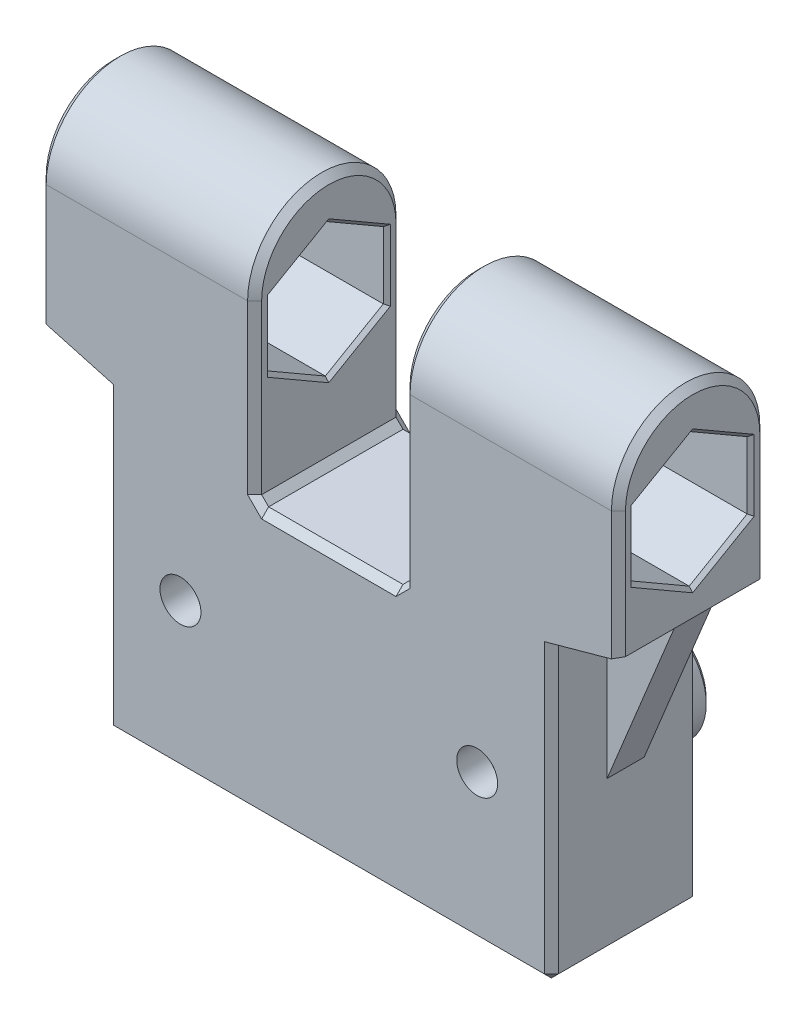
SolidWorks part; units mm, degrees
ref_plane "Front Plane" through (0, 0, 0) normal (0, 0, 1) x (1, 0, 0)
ref_plane "Top Plane" through (0, 0, 0) normal (0, 1, 0) x (1, 0, 0)
ref_plane "Right Plane" through (0, 0, 0) normal (1, 0, 0) x (0, 0, -1)
sketch "Sketch1" plane through (0, 0, 0) normal (0, 1, 0) x (1, 0, 0)
  line L0 (12.7, 0) -> (-12.7, 0) construction
  line L1 (0, 0) -> (0, 3.6469) construction
  line L3 (19.05, -6.35) -> (-19.05, -6.35)
  line L4 (19.05, -6.35) -> (19.05, 6.35)
  line L5 (19.05, 6.35) -> (-19.05, 6.35)
  line L6 (-19.05, -6.35) -> (-19.05, 6.35)
  line L7 (19.05, -6.35) -> (-19.05, 6.35) construction
  line L8 (19.05, 6.35) -> (-19.05, -6.35) construction
  circle A0 centre (12.7, 0) radius 4.05
  circle A1 centre (-12.7, 0) radius 4.05
  point P4 (0, 0)
  dimension "D2" = 8.1
  dimension "D1" = 25.4
  dimension "D3" = 38.1
  dimension "D4" = 12.7
extrude "Boss-Extrude1" add sketch "Sketch1" along normal blind 25.4
sketch "Sketch5" plane through (0, 0, 6.35) normal (0, 0, 1) x (1, 0, 0)
  line L0 (19.05, 12.7) -> (-19.05, 12.7) construction
  line L1 (19.05, 25.4) -> (19.05, 0) construction
  line L2 (-19.05, 25.4) -> (-19.05, 0) construction
  line L3 (0, 0) -> (0, 25.4) construction
  line L4 (-19.05, 0) -> (19.05, 0) construction
  line L5 (-19.05, 25.4) -> (19.05, 25.4) construction
  line L6 (12.7, 0) -> (12.7, 25.4) construction
  circle A0 centre (12.7, 12.7) radius 6.35
  circle A1 centre (-12.7, 12.7) radius 6.35
  circle A2 centre (12.7, 12.7) radius 1.7526
  circle A3 centre (-12.7, 12.7) radius 1.7526
  dimension "D2" = 12.7
  dimension "D3" = 3.5052
  dimension "D1" = 12.7
extrude "Cut-Extrude2" cut sketch "Sketch5" against normal through all contours A2 | A3
sketch "Sketch6" plane through (0, 25.4, 0) normal (0, 1, 0) x (1, 0, 0)
  line L0 (0, 6.35) -> (0, -6.35) construction
  line L1 (19.05, 6.35) -> (-19.05, 6.35) construction
  line L2 (-19.05, -6.35) -> (19.05, -6.35) construction
  line L4 (24.792, -6.35) -> (-24.792, -6.35)
  line L5 (24.792, -6.35) -> (24.792, 6.35)
  line L6 (24.792, 6.35) -> (-24.792, 6.35)
  line L7 (-24.792, -6.35) -> (-24.792, 6.35)
  line L8 (24.792, -6.35) -> (-24.792, 6.35) construction
  line L9 (24.792, 6.35) -> (-24.792, -6.35) construction
  point P6 (0, 0)
  dimension "D1" = 49.584
extrude "Boss-Extrude4" add sketch "Sketch6" along normal blind 19.05
sketch "Sketch7" plane through (-24.792, 0, 0) normal (-1, 0, 0) x (0, 0, 1)
  line L0 (0, 25.4) -> (0, 44.45) construction
  line L1 (-6.35, 25.4) -> (6.35, 25.4) construction
  line L2 (-6.35, 44.45) -> (6.35, 44.45) construction
  line L3 (-6.35, 34.925) -> (6.35, 34.925) construction
  line L4 (-6.35, 44.45) -> (-6.35, 25.4) construction
  line L5 (6.35, 44.45) -> (6.35, 25.4) construction
  line L7 (0, 40.6552) -> (-4.9625, 37.7901)
  line L8 (-4.9625, 37.7901) -> (-4.9625, 32.0599)
  line L9 (-4.9625, 32.0599) -> (0, 29.1948)
  line L10 (0, 29.1948) -> (4.9625, 32.0599)
  line L11 (4.9625, 32.0599) -> (4.9625, 37.7901)
  line L12 (4.9625, 37.7901) -> (0, 40.6552)
  circle A0 centre (0, 34.925) radius 4.9625 construction
  dimension "D1" = 9.925
extrude "Cut-Extrude3" cut sketch "Sketch7" against normal through all
sketch "Sketch8" plane through (-24.792, 0, 0) normal (-1, 0, 0) x (0, 0, 1)
  line L0 (4.9625, 37.7901) -> (-4.9625, 37.7901) construction
  line L1 (-6.35, 37.7901) -> (-6.35, 44.45)
  line L2 (-6.35, 44.45) -> (6.35, 44.45)
  line L3 (6.35, 44.45) -> (6.35, 37.7901)
  arc A0 (6.35, 37.7901) -> (-6.35, 37.7901) centre (0, 37.7901) ccw
extrude "Cut-Extrude4" cut sketch "Sketch8" against normal through all
sketch "Sketch9" plane through (0, 0, -6.35) normal (0, 0, -1) x (-1, 0, 0)
  line L0 (0, 37.7901) -> (0, 0) construction
  line L1 (-24.792, 37.7901) -> (24.792, 37.7901) construction
  line L2 (19.05, 25.4) -> (24.792, 26.9875)
  line L3 (24.792, 37.7901) -> (24.792, 25.4) construction
  line L4 (24.792, 26.9875) -> (24.792, 25.4)
  line L5 (24.792, 25.4) -> (19.05, 25.4)
  line L6 (-24.792, 25.4) -> (-19.05, 25.4)
  line L7 (-24.792, 26.9875) -> (-24.792, 25.4)
  line L8 (-19.05, 25.4) -> (-24.792, 26.9875)
  dimension "D1" = 1.5875
extrude "Cut-Extrude5" cut sketch "Sketch9" against normal through all
chamfer "Chamfer1" distance 0.6 angle 45 17 edges at (19.05, 0, 0) (24.792, 32.3888, 6.35) (24.792, 44.1401, 0) (24.792, 32.3888, -6.35) (-24.792, 32.3888, 6.35) (-24.792, 44.1401, 0) (-24.792, 32.3888, -6.35) (0, 0, 6.35) (0, 0, -6.35) (-19.05, 0, 0)
sketch "Sketch10" plane through (0, 0, 6.35) normal (0, 0, 1) x (1, 0, 0)
  line L0 (0, 0.6) -> (0, 37.7901) construction
  line L1 (-18.45, 0.6) -> (18.45, 0.6) construction
  line L2 (24.192, 37.7901) -> (-24.192, 37.7901) construction
  line L4 (-6.35, 48.225) -> (6.35, 48.225)
  line L5 (-6.35, 48.225) -> (-6.35, 22.825)
  line L6 (-6.35, 22.825) -> (6.35, 22.825)
  line L7 (6.35, 48.225) -> (6.35, 22.825)
  line L8 (-6.35, 48.225) -> (6.35, 22.825) construction
  line L9 (-6.35, 22.825) -> (6.35, 48.225) construction
  point P6 (0, 35.525)
  dimension "D1" = 25.4
  dimension "D2" = 12.7
  dimension "D3" = 34.925
extrude "Cut-Extrude6" cut sketch "Sketch10" against normal through all
chamfer "Chamfer2" distance 0.6 angle 45 10 edges at (-6.35, 44.1401, 0) (6.35, 44.1401, 0) (-6.35, 30.3076, 6.35) (6.35, 30.3076, 6.35) (-6.35, 30.3076, -6.35) (6.35, 30.3076, -6.35) (0, 22.825, 6.35) (-6.35, 22.825, 0) (0, 22.825, -6.35) (6.35, 22.825, 0)
chamfer "Chamfer3" distance 0.3 angle 45 24 edges at (24.792, 39.2227, -2.4812) (24.792, 39.2227, 2.4812) (24.792, 34.925, 4.9625) (24.792, 30.6273, 2.4812) (24.792, 30.6273, -2.4812) (24.792, 34.925, -4.9625) (-24.792, 34.925, -4.9625) (-24.792, 30.6273, -2.4812) (-24.792, 30.6273, 2.4812) (-24.792, 34.925, 4.9625) (-24.792, 39.2227, 2.4812) (-24.792, 39.2227, -2.4812) (-6.35, 30.6273, 2.4812) (-6.35, 34.925, 4.9625) (-6.35, 39.2227, 2.4812) (-6.35, 39.2227, -2.4812) (-6.35, 30.6273, -2.4812) (-6.35, 34.925, -4.9625) (6.35, 30.6273, 2.4812) (6.35, 34.925, 4.9625) (6.35, 39.2227, 2.4812) (6.35, 30.6273, -2.4812) (6.35, 34.925, -4.9625) (6.35, 39.2227, -2.4812)
sketch "Sketch11" plane through (-19.05, 0, 0) normal (-1, 0, 0) x (0, 0, 1)
  line L0 (0, 25.4) -> (0, 0.6) construction
  line L1 (-5.75, 25.4) -> (5.75, 25.4) construction
  line L2 (-5.75, 0.6) -> (5.75, 0.6) construction
ref_plane "Plane1" through (0, 0, 0) normal (0, 0, -1) x (0, -1, 0)
sketch "Sketch13" plane through (0, 0, 0) normal (0, 0, -1) x (0, -1, 0)
  line L0 (-25.4, 19.05) -> (-26.9875, 24.792)
  line L1 (-26.9875, 24.792) -> (-13, 19.05)
  line L2 (-25.4, 19.05) -> (-0.6, 19.05) construction
  line L3 (-22.225, 0) -> (0, 0) construction
  line L4 (-22.225, -5.75) -> (-22.225, 5.75) construction
  line L5 (-26.9875, -24.792) -> (-13, -19.05)
  line L6 (-25.4, -19.05) -> (-26.9875, -24.792)
  line L7 (-25.4, 19.05) -> (-13, 19.05)
  line L8 (-13, -19.05) -> (-25.4, -19.05)
extrude "Boss-Extrude5" add sketch "Sketch13" along normal blind 1.5875 and the other way blind 1.5875
sketch "Sketch14" plane through (0, 0, -6.35) normal (0, 0, -1) x (-1, 0, 0)
  circle A0 centre (-12.7, 12.7) radius 4.7625
  circle A1 centre (12.7, 12.7) radius 4.7625
  dimension "D1" = 9.525
  dimension "D2" = 9.525
extrude "Boss-Extrude6" add sketch "Sketch14" along normal blind 2.54
sketch "Sketch15" plane through (0, 0, 6.35) normal (0, 0, 1) x (1, 0, 0)
  circle A0 centre (12.7, 12.7) radius 1.7526
  circle A1 centre (-12.7, 12.7) radius 1.7526
extrude "Cut-Extrude7" cut sketch "Sketch15" against normal through all
chamfer "Chamfer4" distance 0.4 angle 45 6 edges at (-7.9375, 12.7, -6.35) (-17.4625, 12.7, -8.89) (-10.9474, 12.7, -8.89) (14.4526, 12.7, -8.89) (17.4625, 12.7, -6.35) (7.9375, 12.7, -8.89)
sketch "Sketch18" plane through (0, 25.4, 0) normal (0, -1, 0) x (1, 0, 0)
  line L0 (0, 5.75) -> (0, -5.75) construction
  line L1 (18.45, 5.75) -> (-18.45, 5.75) construction
  line L2 (-18.45, -5.75) -> (18.45, -5.75) construction
  circle A0 centre (-12.7, 0) radius 4.1
  circle A1 centre (12.7, 0) radius 4.1
  dimension "D1" = 8.2
extrude "Boss-Extrude7" add sketch "Sketch18" along normal blind 6.35
